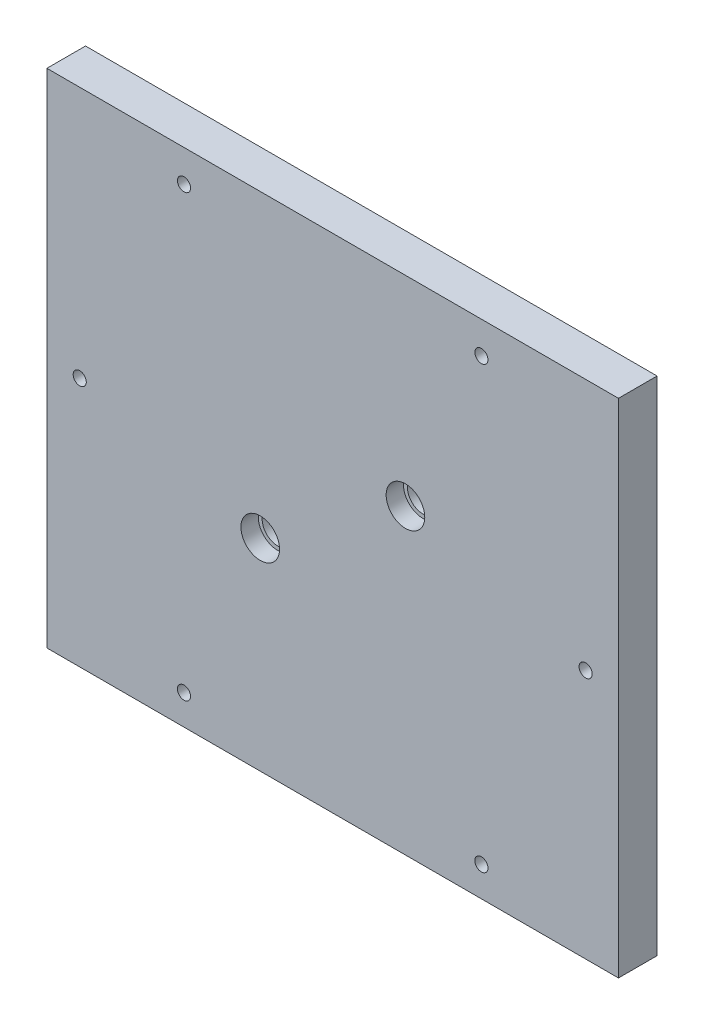
SolidWorks part; units mm, degrees
material "PVC Rígido"
ref_plane "Plano frontal" through (0, 0, 0) normal (0, 0, 1) x (1, 0, 0)
ref_plane "Plano superior" through (0, 0, 0) normal (0, 1, 0) x (1, 0, 0)
ref_plane "Plano direito" through (0, 0, 0) normal (1, 0, 0) x (0, 0, -1)
sketch "Esboço1" plane through (0, 0, 0) normal (0, 0, 1) x (1, 0, 0)
  line L1 (-74.0034, 189.2634) -> (73.9966, 189.2634)
  line L2 (-74.0034, 189.2634) -> (-74.0034, 59.2634)
  line L3 (-74.0034, 59.2634) -> (73.9966, 59.2634)
  line L4 (73.9966, 189.2634) -> (73.9966, 59.2634)
  dimension "D1" = 148
  dimension "D2" = 130
extrude "Ressalto-extrusão1" add sketch "Esboço1" along normal blind 10
hole_wizard "Furo com folga de M3X0.5" positions "Esboço3" profile "Esboço2" hole size "M3" standard "Métrico Ansi" end condition up to next
sketch "Esboço3" plane through (0, 0, 10) normal (0, 0, 1) x (1, 0, 0)
  point P0 (38.5, 67)
  point P1 (-38.5068, 67)
  point P4 (65.5, 124)
  point P7 (-65.5068, 124)
  point P10 (-38.5068, 181)
  point P13 (38.5, 181)
sketch "Esboço2" plane through (38.5, 67, 10) normal (1, 0, 0) x (0, -1, 0)
  line L0 (0, 0) -> (0, 10)
  line L1 (0, 10) -> (1.7, 10)
  line L2 (1.7, 10) -> (1.7, 0)
  line L5 (1.7, 0) -> (0, 0)
  line L11 (0, -6.35) -> (0, 107.95) construction
  dimension "Thru Hole Dia." = 3.4
  dimension "Thru Hole Depth" = 10
sketch "Esboço5" plane through (0, 0, 10) normal (0, 0, 1) x (1, 0, 0)
  line L0 (-74.0034, 59.2634) -> (73.9966, 59.2634) construction
  line L1 (-74.0034, 189.2634) -> (-74.0034, 59.2634) construction
  circle A0 centre (-18.7634, 111.5234) radius 5
  circle A1 centre (18.8366, 137.5034) radius 5
  dimension "D1" = 10
  dimension "D2" = 10
  dimension "D3" = 52.26
  dimension "D4" = 55.24
  dimension "D5" = 78.24
  dimension "D6" = 92.84
extrude "Corte-extrusão1" cut sketch "Esboço5" against normal blind 4.5
sketch "Esboço6" plane through (0, 0, 10) normal (0, 0, 1) x (1, 0, 0)
  circle A0 centre (-18.7634, 111.5234) radius 4
  circle A1 centre (18.8366, 137.5034) radius 4
  dimension "D1" = 8
  dimension "D2" = 8
extrude "Corte-extrusão2" cut sketch "Esboço6" against normal up to next
